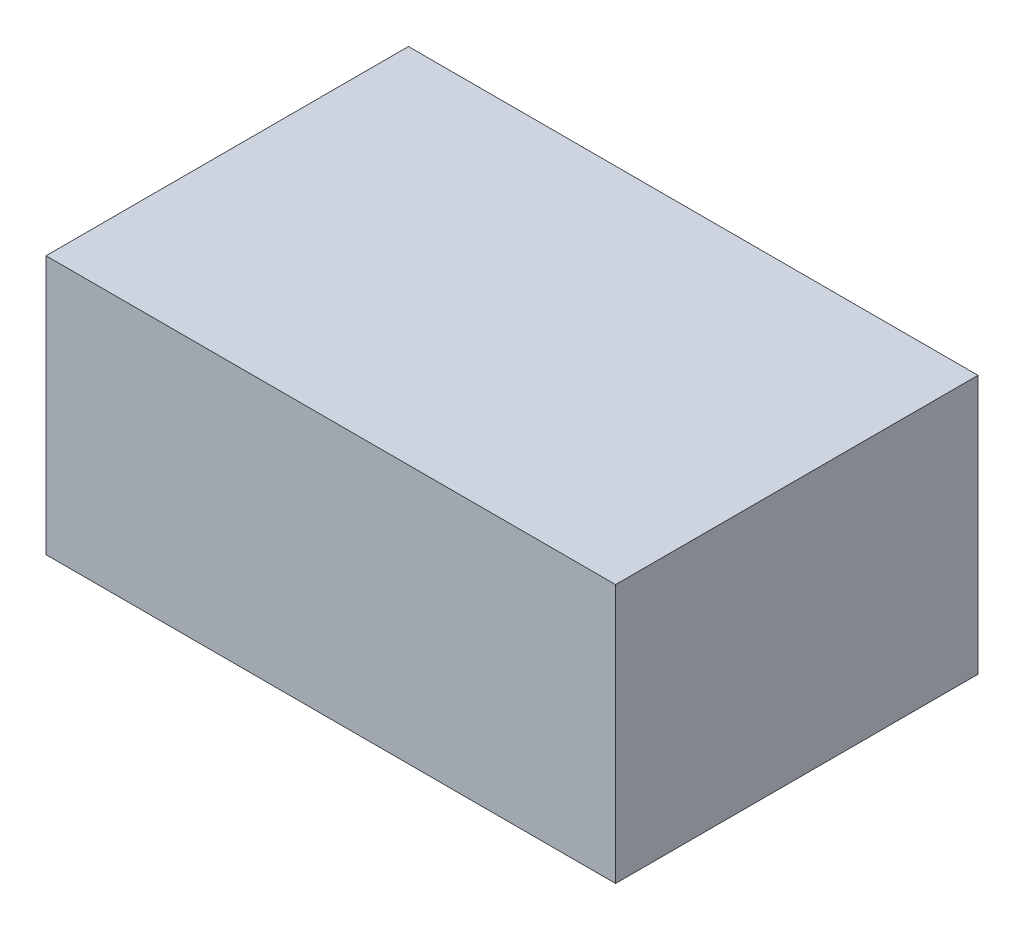
SolidWorks part; units mm, degrees
ref_plane "前视基准面" through (0, 0, 0) normal (0, 0, 1) x (1, 0, 0)
ref_plane "上视基准面" through (0, 0, 0) normal (0, 1, 0) x (1, 0, 0)
ref_plane "右视基准面" through (0, 0, 0) normal (1, 0, 0) x (0, 0, -1)
other "Configuration Table"
sketch "草图1" plane through (0, 0, 0) normal (0, 0, 1) x (1, 0, 0)
  line L1 (-27.5, -12.5) -> (27.5, -12.5)
  line L2 (-27.5, -12.5) -> (-27.5, 12.5)
  line L3 (-27.5, 12.5) -> (27.5, 12.5)
  line L4 (27.5, -12.5) -> (27.5, 12.5)
  line L5 (-27.5, -12.5) -> (27.5, 12.5) construction
  line L6 (-27.5, 12.5) -> (27.5, -12.5) construction
  point P0 (0, 0)
extrude "凸台-拉伸1" add sketch "草图1" along normal blind 35
